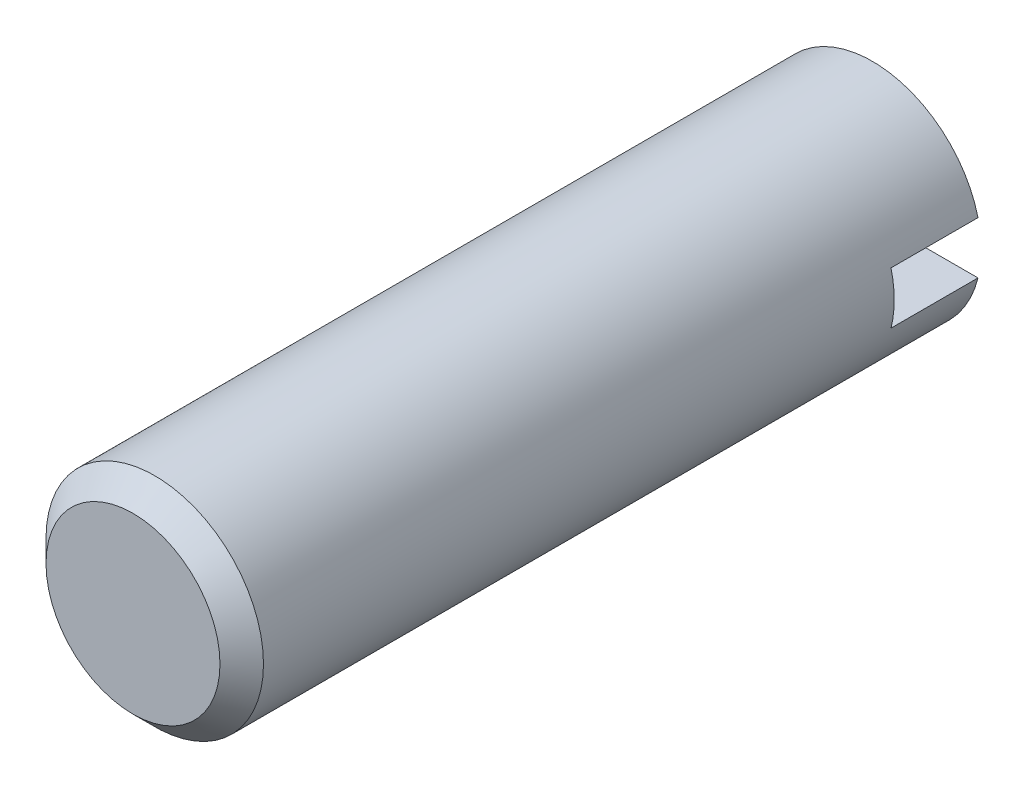
SolidWorks part; units mm, degrees
material "17CrNiMo6"
ref_plane "Front Plane" through (0, 0, 0) normal (0, 0, 1) x (1, 0, 0)
ref_plane "Top Plane" through (0, 0, 0) normal (0, 1, 0) x (1, 0, 0)
ref_plane "Right Plane" through (0, 0, 0) normal (1, 0, 0) x (0, 0, -1)
sketch "Sketch1" plane through (0, 0, 0) normal (1, 0, 0) x (0, 0, -1)
  line L0 (0, 0) -> (54.1659, 0) construction
  line L1 (0, 0) -> (0, 2)
  line L2 (0, 2) -> (0.5, 2.5)
  line L3 (0.5, 2.5) -> (17, 2.5)
  line L4 (17, 2.5) -> (17, 0)
  line L5 (0, 0) -> (17, 0)
  dimension "D1" = 5
  dimension "D2" = 0.5
  dimension "D3" = 45
  dimension "D4" = 17
revolve "Revolve1" add sketch "Sketch1" angle 360 about L0
cosmetic thread "Cosmetic Thread1" parameters "D2"=4.2
sketch "Sketch2" plane through (0, 0, -17) normal (0, 0, -1) x (-1, 0, 0)
  line L0 (0, 0) -> (4.1575, 0) construction
  line L1 (-2.7124, 0.6) -> (2.7124, 0.6)
  line L2 (-2.7124, 0.6) -> (-2.7124, -0.6)
  line L3 (-2.7124, -0.6) -> (2.7124, -0.6)
  line L4 (2.7124, 0.6) -> (2.7124, -0.6)
  line L5 (0, 0) -> (0, 1.4043) construction
  dimension "D1" = 5.4248
  dimension "D2" = 1.2
extrude "Cut-Extrude1" cut sketch "Sketch2" against normal blind 2
